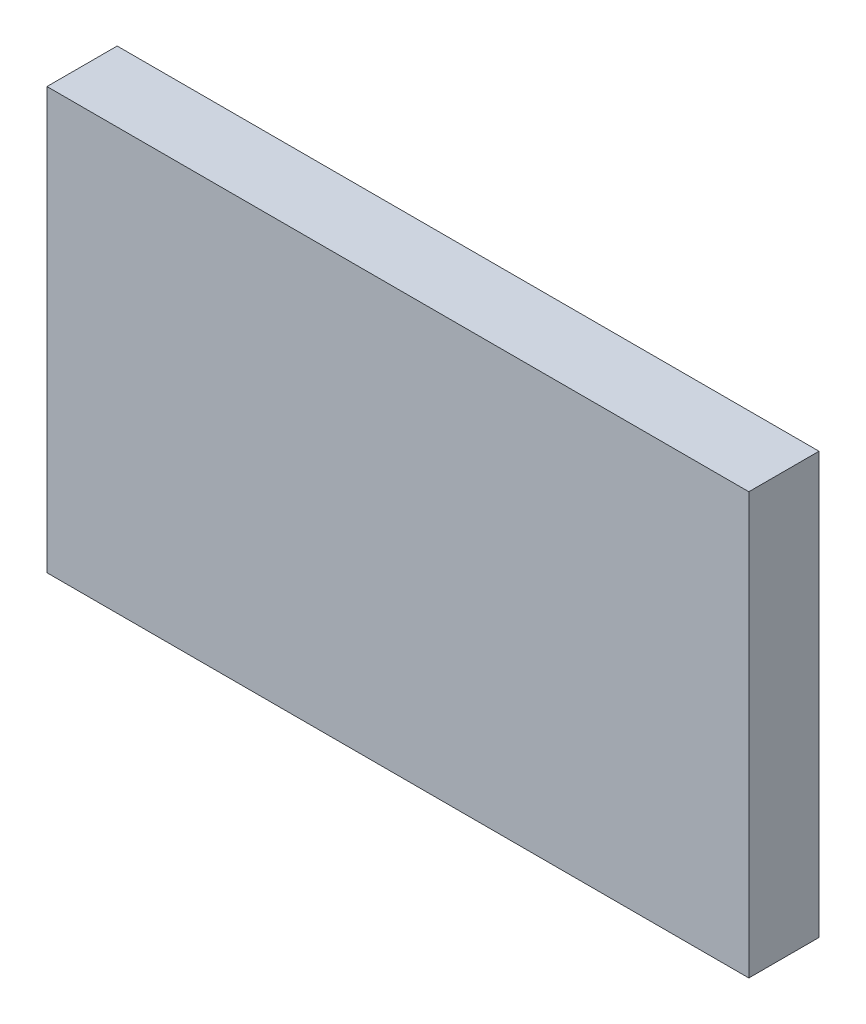
SolidWorks part; units mm, degrees
material "AISI 1020"
ref_plane "前视基准面" through (0, 0, 0) normal (0, 0, 1) x (1, 0, 0)
ref_plane "上视基准面" through (0, 0, 0) normal (0, 1, 0) x (1, 0, 0)
ref_plane "右视基准面" through (0, 0, 0) normal (1, 0, 0) x (0, 0, -1)
other "Configuration Table"
sketch "草图8" plane through (0, 0, 0) normal (0, 0, 1) x (1, 0, 0)
  line L1 (-50, 30) -> (50, 30)
  line L2 (-50, 30) -> (-50, -30)
  line L3 (-50, -30) -> (50, -30)
  line L4 (50, 30) -> (50, -30)
extrude "凸台-拉伸1" add sketch "草图8" along normal blind 10
